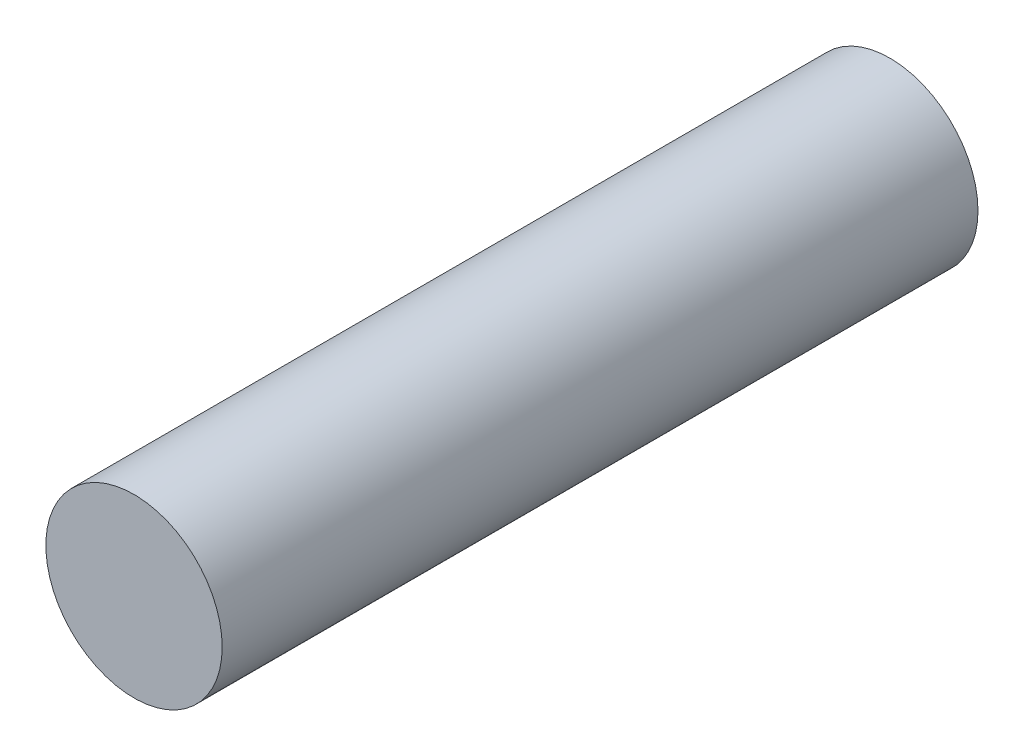
SolidWorks part; units mm, degrees
ref_plane "前视基准面" through (0, 0, 0) normal (0, 0, 1) x (1, 0, 0)
ref_plane "上视基准面" through (0, 0, 0) normal (0, 1, 0) x (1, 0, 0)
ref_plane "右视基准面" through (0, 0, 0) normal (1, 0, 0) x (0, 0, -1)
other "Configuration Table"
sketch "草图1" plane through (0, 0, 0) normal (0, 0, 1) x (1, 0, 0)
  circle A0 centre (0, 0) radius 0.7
extrude "凸台-拉伸1" add sketch "草图1" along normal blind 6
